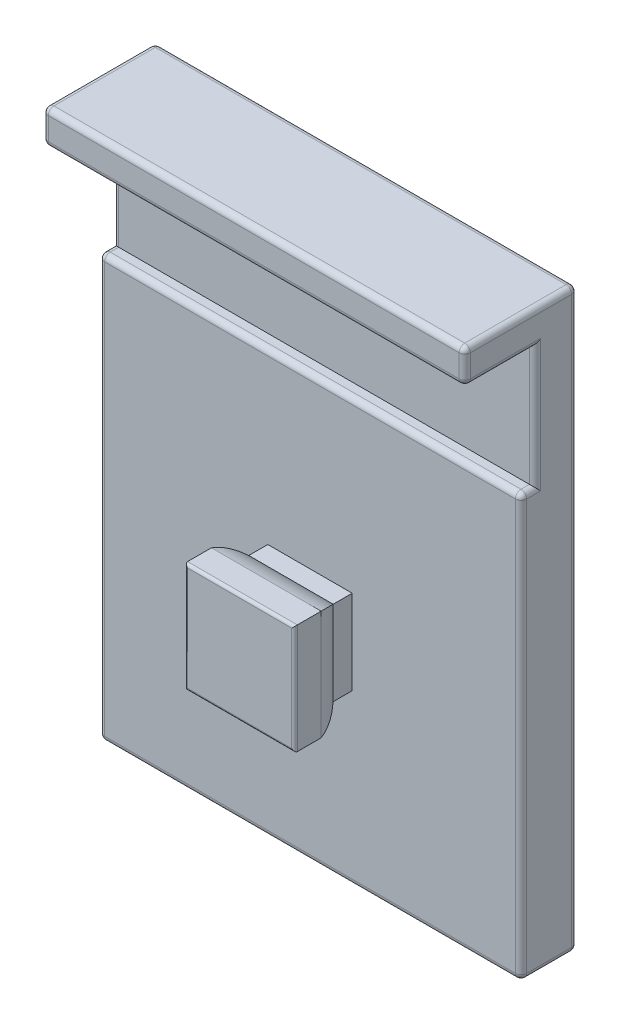
SolidWorks part; units mm, degrees
ref_plane "前视基准面" through (0, 0, 0) normal (0, 0, 1) x (1, 0, 0)
ref_plane "上视基准面" through (0, 0, 0) normal (0, 1, 0) x (1, 0, 0)
ref_plane "右视基准面" through (0, 0, 0) normal (1, 0, 0) x (0, 0, -1)
sketch "草图1" plane through (0, 0, 0) normal (0, 0, 1) x (1, 0, 0)
  line L1 (-7.5, -7.5) -> (7.5, -7.5)
  line L2 (-7.5, -7.5) -> (-7.5, 7.5)
  line L3 (-7.5, 7.5) -> (7.5, 7.5)
  line L4 (7.5, -7.5) -> (7.5, 7.5)
extrude "凸台-拉伸1" add sketch "草图1" against normal blind 2
sketch "草图2" plane through (0, 0, 0) normal (0, 0, 1) x (1, 0, 0)
  line L1 (-1.5, -1.5) -> (1.5, -1.5)
  line L2 (-1.5, -1.5) -> (-1.5, 1.5)
  line L3 (-1.5, 1.5) -> (1.5, 1.5)
  line L4 (1.5, -1.5) -> (1.5, 1.5)
extrude "凸台-拉伸2" add sketch "草图2" along normal blind 1
sketch "草图3" plane through (0, 0, 0) normal (0, 1, 0) x (1, 0, 0)
  line L0 (-1.95, -2.5) -> (1.95, -2.5)
  line L1 (-1.95, -2.5) -> (-1.95, -1.5556)
  line L2 (-1.5, -1) -> (-1.5, 0) construction
  line L3 (-1.5, -0.6771) -> (1.5, -0.6771)
  line L4 (1.95, -2.5) -> (1.95, -1.5556)
  arc A0 (1.95, -1.5556) -> (1.5, -0.6771) centre (0, -2) ccw
  arc A1 (-1.5, -0.6771) -> (-1.95, -1.5556) centre (0, -2) ccw
extrude "凸台-拉伸3" add sketch "草图3" along normal blind 2 and the other way blind 2
sketch "草图4" plane through (0, 0, 0) normal (1, 0, 0) x (0, 0, -1)
  line L0 (-2.5, 1.95) -> (-1.5556, 1.95)
  line L1 (-2.5, 1.95) -> (-2.5, 2)
  line L2 (-2.5, -2) -> (-2.5, 2) construction
  line L3 (-2.5, 2) -> (-0.6771, 2)
  line L4 (-0.6771, 2) -> (-0.6771, 1.5)
  line L5 (-2.5, -2) -> (-0.6771, -2)
  line L6 (-0.6771, -2) -> (-0.6771, -1.5)
  line L7 (-2.5, -1.95) -> (-1.5556, -1.95)
  line L8 (-2.5, -1.95) -> (-2.5, -2)
  arc A0 (-0.6771, 1.5) -> (-1.5556, 1.95) centre (-2, 0) ccw
  arc A2 (-1.5556, -1.95) -> (-0.6771, -1.5) centre (-2, 0) ccw
extrude "切除-拉伸1" cut sketch "草图4" against normal up to next and the other way up to next
fillet "圆角1" radius 0.1 4 edges at (0, -1.95, 2.5) (-1.95, 0, 2.5) (0, 1.95, 2.5) (1.95, 0, 2.5)
sketch "草图5" plane through (0, 7.5, 0) normal (0, 1, 0) x (1, 0, 0)
  line L0 (7.5, 2) -> (7.5, 0) construction
  line L1 (-7.5, 2) -> (7.5, 2)
  line L2 (-7.5, 2) -> (-7.5, 0.5)
  line L3 (-7.5, 0.5) -> (7.5, 0.5)
  line L4 (7.5, 2) -> (7.5, 0.5)
extrude "凸台-拉伸4" add sketch "草图5" along normal blind 5.5
sketch "草图6" plane through (0, 0, -0.5) normal (0, 0, 1) x (1, 0, 0)
  line L0 (7.5, 13) -> (7.5, 7.5) construction
  line L1 (-7.5, 13) -> (7.5, 13)
  line L2 (-7.5, 13) -> (-7.5, 11.8)
  line L3 (-7.5, 11.8) -> (7.5, 11.8)
  line L4 (7.5, 13) -> (7.5, 11.8)
extrude "凸台-拉伸5" add sketch "草图6" along normal blind 2.5
fillet "圆角2" radius 0.2 22 edges at (0, -7.5, -2) (0, -7.5, 0) (-7.5, -7.5, -1) (-7.5, 2.75, -2) (-7.5, 12.4, 2) (-7.5, 11.8, 0.75) (-7.5, 0, 0) (7.5, 11.8, 0.75) (7.5, 12.4, 2) (7.5, 2.75, -2) (7.5, -7.5, -1) (7.5, 0, 0) (0, 13, -2) (7.5, 13, 0) (0, 13, 2) (-7.5, 13, 0) (0, 7.5, 0) (0, 11.8, 2)
